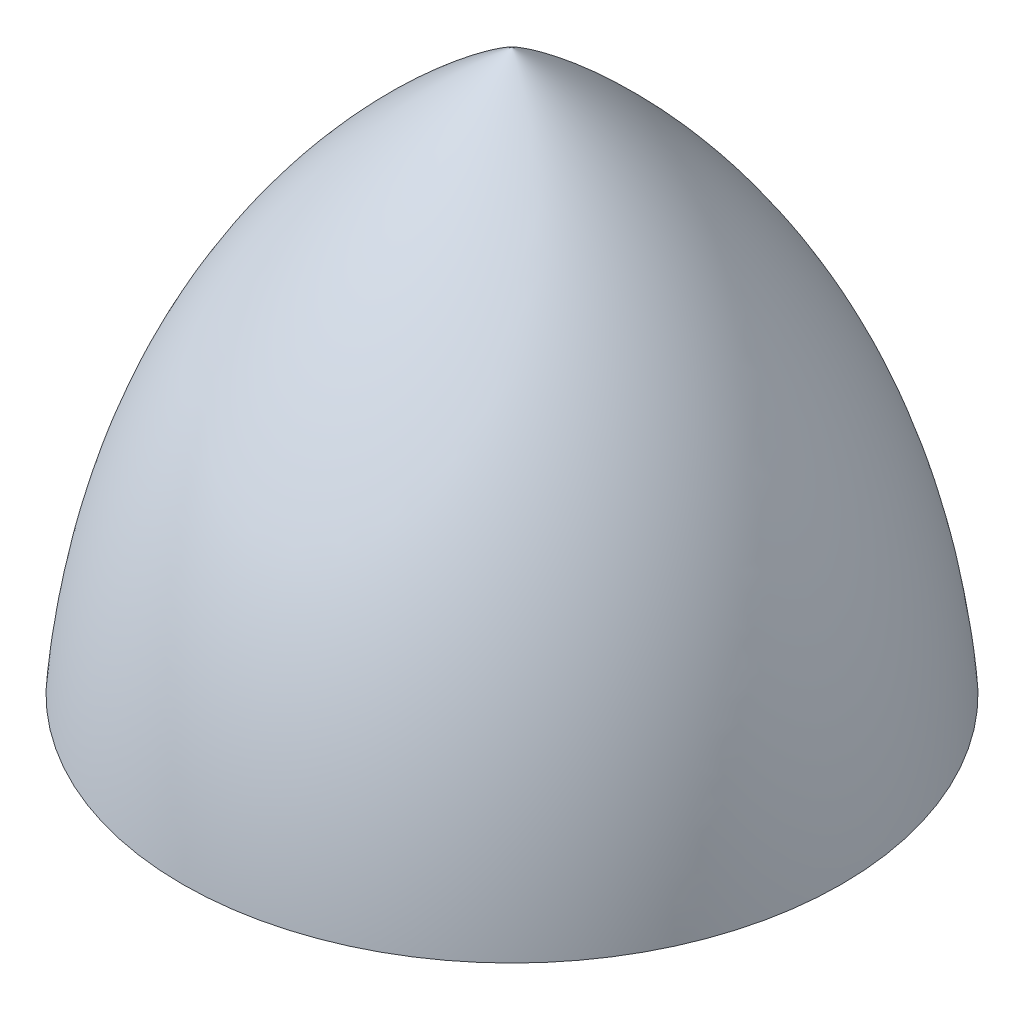
SolidWorks part; units mm, degrees
ref_plane "Front Plane" through (0, 0, 0) normal (0, 0, 1) x (1, 0, 0)
ref_plane "Top Plane" through (0, 0, 0) normal (0, 1, 0) x (1, 0, 0)
ref_plane "Right Plane" through (0, 0, 0) normal (1, 0, 0) x (0, 0, -1)
sketch "Sketch1" plane through (0, 0, 0) normal (0, 0, 1) x (1, 0, 0)
  line L0 (0, 286.8781) -> (0, -85.7405) construction
  line L2 (400, 0) -> (500, 0)
  line L3 (0, 750) -> (0, 850)
  spline S0 degree 2 poles (0, 750) (357.7105, 458.3852) (400, 0) knots 0 0 0 1 1 1
  spline S1 degree 2 poles (0, 850) (452.2286, 543.9168) (500, 0) knots 0 0 0 1 1 1
  dimension "D1" = 750
  dimension "D2" = 400
  dimension "D3" = 100
  dimension "D4" = 100
revolve "Revolve1" add sketch "Sketch1" angle 360 about L0
